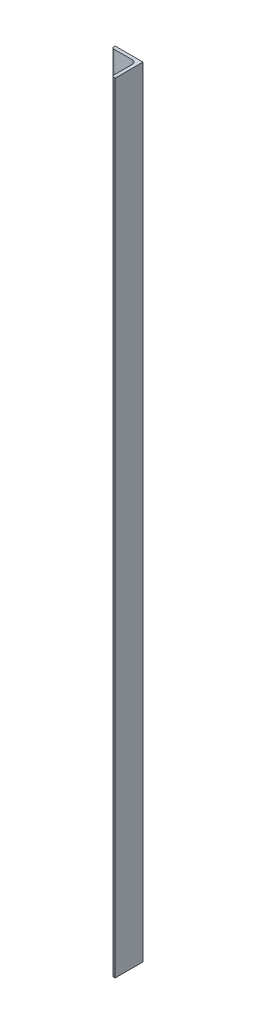
SolidWorks part; units mm, degrees
ref_plane "Front Plane" through (0, 0, 0) normal (0, 0, 1) x (1, 0, 0)
ref_plane "Top Plane" through (0, 0, 0) normal (0, 1, 0) x (1, 0, 0)
ref_plane "Right Plane" through (0, 0, 0) normal (1, 0, 0) x (0, 0, -1)
sketch "Sketch1" plane through (0, 0, 0) normal (0, 1, 0) x (1, 0, 0)
  line L6 (0, 0) -> (-50, 0)
  line L10 (0, 0) -> (0, -50)
  line L11 (0, -50) -> (-2.5, -50)
  line L12 (-50, 0) -> (-50, -2.5)
  line L15 (-46.5, -6) -> (-13, -6)
  line L16 (-6, -46.5) -> (-6, -13)
  arc A8 (-13, -6) -> (-6, -13) centre (-13, -13) cw
  arc A9 (-2.5, -50) -> (-6, -46.5) centre (-2.5, -46.5) cw
  arc A10 (-50, -2.5) -> (-46.5, -6) centre (-46.5, -2.5) ccw
  dimension "D4" = 6
  dimension "D5" = 7
  dimension "D6" = 3.5
  dimension "D1" = 50
  dimension "D2" = 50
  dimension "D3" = 6
extrude "Boss-Extrude1" add sketch "Sketch1" along normal mid plane 1400
sketch "Sketch2" plane through (0, 0, 0) normal (0, 0, -1) x (-1, 0, 0)
  line L0 (50, 700) -> (50, -700) construction
  line L1 (55, 0) -> (-55, 0) construction
  circle A0 centre (30, 52.92) radius 6
  circle A1 centre (30, -52.92) radius 6
  dimension "D1" = 12
  dimension "D2" = 20
  dimension "D3" = 52.92
extrude "Cut-Extrude1" cut sketch "Sketch2" against normal up to next
